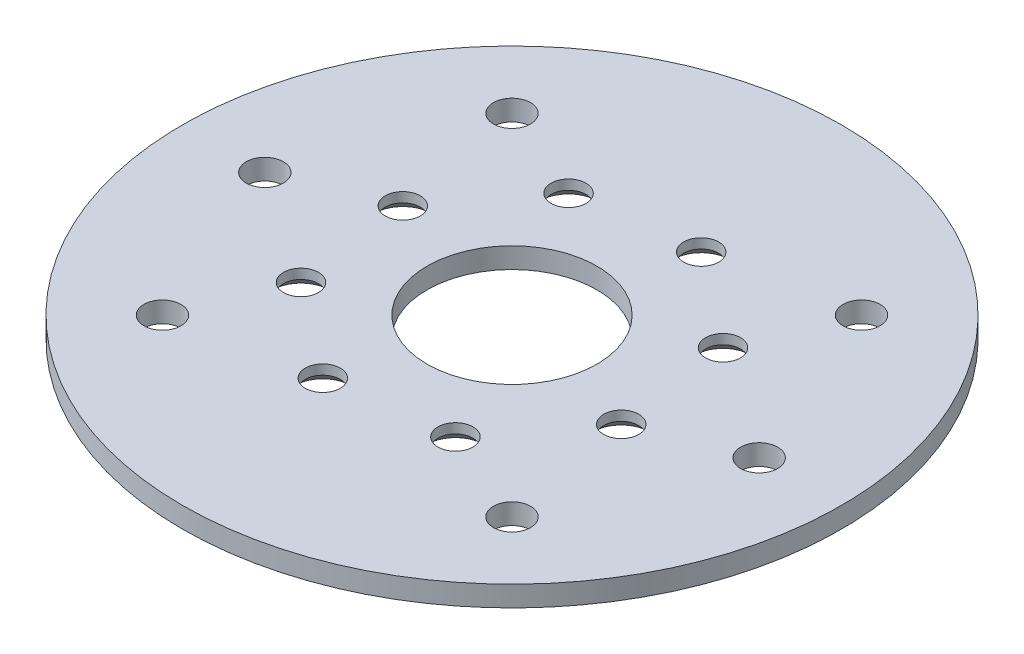
SolidWorks part; units mm, degrees
ref_plane "Front Plane" through (0, 0, 0) normal (0, 0, 1) x (1, 0, 0)
ref_plane "Top Plane" through (0, 0, 0) normal (0, 1, 0) x (1, 0, 0)
ref_plane "Right Plane" through (0, 0, 0) normal (1, 0, 0) x (0, 0, -1)
sketch "Sketch1" plane through (0, 0, 0) normal (0, 1, 0) x (1, 0, 0)
  circle A0 centre (0, 0) radius 8.25
  circle A1 centre (0, 0) radius 32
  dimension "D1" = 16.5
  dimension "D2" = 64
extrude "Boss-Extrude1" add sketch "Sketch1" along normal blind 2
sketch "Sketch2" plane through (0, 2, 0) normal (0, 1, 0) x (1, 0, 0)
  circle A0 centre (0, 21) radius 4
  circle A1 centre (0, 0) radius 21 construction
  circle A2 centre (18.1865, 10.5) radius 4
  circle A3 centre (18.1865, -10.5) radius 4
  circle A4 centre (0, -21) radius 4
  circle A5 centre (-18.1865, -10.5) radius 4
  circle A6 centre (-18.1865, 10.5) radius 4
  point P17 (0, 0)
  dimension "D1" = 8
  dimension "D2" = 42
  dimension "D3" = 6
extrude "Cut-Extrude1" [suppressed] cut sketch "Sketch2" against normal through all and the other way through all
hole_wizard "CSK for M3 Hex Socket Countersunk Head Screw1" positions "Sketch3" profile "Sketch4" countersink size "M3" standard "DIN" end condition up to next
sketch "Sketch3" plane through (0, 0, 0) normal (0, 1, 0) x (1, 0, 0)
  line L0 (0, 0) -> (32.7202, 18.891) construction
  circle A0 centre (0, 0) radius 15
  point P8 (12.9904, 7.5)
  point P14 (14.4889, -3.8823)
  point P15 (7.5, -12.9904)
  point P16 (-3.8823, -14.4889)
  point P17 (-12.9904, -7.5)
  point P18 (-14.4889, 3.8823)
  point P19 (-7.5, 12.9904)
  point P20 (3.8823, 14.4889)
  dimension "D2" = 30
  dimension "D1" = 30
  dimension "D3" = 8
sketch "Sketch4" plane through (3.8823, 0, -14.4889) normal (1, 0, 0) x (0, 0, -1)
  line L0 (0, 0) -> (0, 2)
  line L1 (0, 2) -> (1.7, 2)
  line L2 (1.7, 2) -> (1.7, 1.05)
  line L3 (1.7, 1.05) -> (2.75, 0)
  line L5 (2.75, 0) -> (0, 0)
  line L6 (-1.7, 1.05) -> (-2.75, 0) construction
  line L11 (0, -6.35) -> (0, 107.95) construction
  dimension "Thru Hole Dia." = 3.4
  dimension "Thru Hole Depth" = 2
  dimension "Near C'Sink Dia." = 5.5
  dimension "Near C'Sink Angle" = 90
hole_wizard "M3 Clearance Hole1" positions "Sketch5" profile "Sketch7" hole size "M3" standard "DIN"
sketch "Sketch5" plane through (0, 0, 0) normal (0, -1, 0) x (-1, 0, 0)
  circle A0 centre (0, 0) radius 24
  point P6 (-24, 0)
  point P14 (-16.9706, 16.9706)
  point P16 (16.9706, 16.9706)
  point P17 (24, 0)
  point P18 (16.9706, -16.9706)
  point P22 (-16.9706, -16.9706)
  point P25 (0, 24) [skipped]
  point P27 (0, -24) [skipped]
  dimension "D1" = 48
  dimension "D2" = 8
sketch "Sketch7" plane through (16.9706, 0, 16.9706) normal (1, 0, 0) x (0, 0, -1)
  line L0 (0, 0) -> (0, 2)
  line L1 (0, 2) -> (1.8, 2)
  line L2 (1.8, 2) -> (1.8, 0)
  line L5 (1.8, 0) -> (0, 0)
  line L11 (0, -6.35) -> (0, 107.95) construction
  dimension "Thru Hole Dia." = 3.6
  dimension "Thru Hole Depth" = 2
hole_wizard "Ø3.2 (3.2) Diameter Hole1" [suppressed] positions "Sketch8" profile "Sketch9" hole size "Ø3.2" standard "DIN"
sketch "Sketch8" plane through (0, 0, 0) normal (0, -1, 0) x (-1, 0, 0)
  circle A0 centre (0, 0) radius 15
  point P5 (0, 15)
  point P12 (12.9904, 7.5)
  point P13 (12.9904, -7.5)
  point P14 (0, -15)
  point P15 (-12.9904, -7.5)
  point P16 (-12.9904, 7.5)
  dimension "D1" = 30
  dimension "D2" = 6
sketch "Sketch9" plane through (12.9904, 0, -7.5) normal (1, 0, 0) x (0, 0, -1)
  line L0 (0, 0) -> (0, 2)
  line L1 (0, 2) -> (1.6, 2)
  line L2 (1.6, 2) -> (1.6, 0)
  line L5 (1.6, 0) -> (0, 0)
  line L11 (0, -6.35) -> (0, 107.95) construction
  dimension "Thru Hole Dia." = 3.2
  dimension "Thru Hole Depth" = 2
